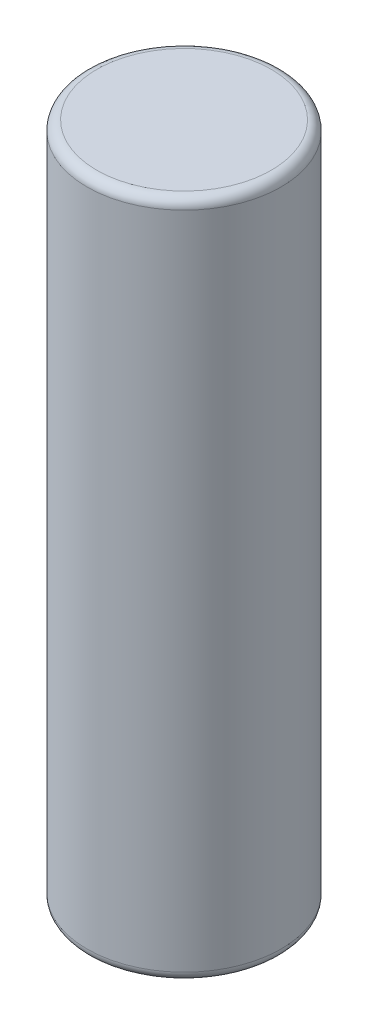
SolidWorks part; units mm, degrees
ref_plane "Front Plane" through (0, 0, 0) normal (0, 0, 1) x (1, 0, 0)
ref_plane "Top Plane" through (0, 0, 0) normal (0, 1, 0) x (1, 0, 0)
ref_plane "Right Plane" through (0, 0, 0) normal (1, 0, 0) x (0, 0, -1)
sketch "Sketch1" plane through (0, 0, 0) normal (0, 1, 0) x (1, 0, 0)
  circle A0 centre (0, 0) radius 1
extrude "Boss-Extrude1" add sketch "Sketch1" along normal blind 7
fillet "Fillet1" radius 0.1 2 edges at (0, 0, 1) (0, 7, 1)
